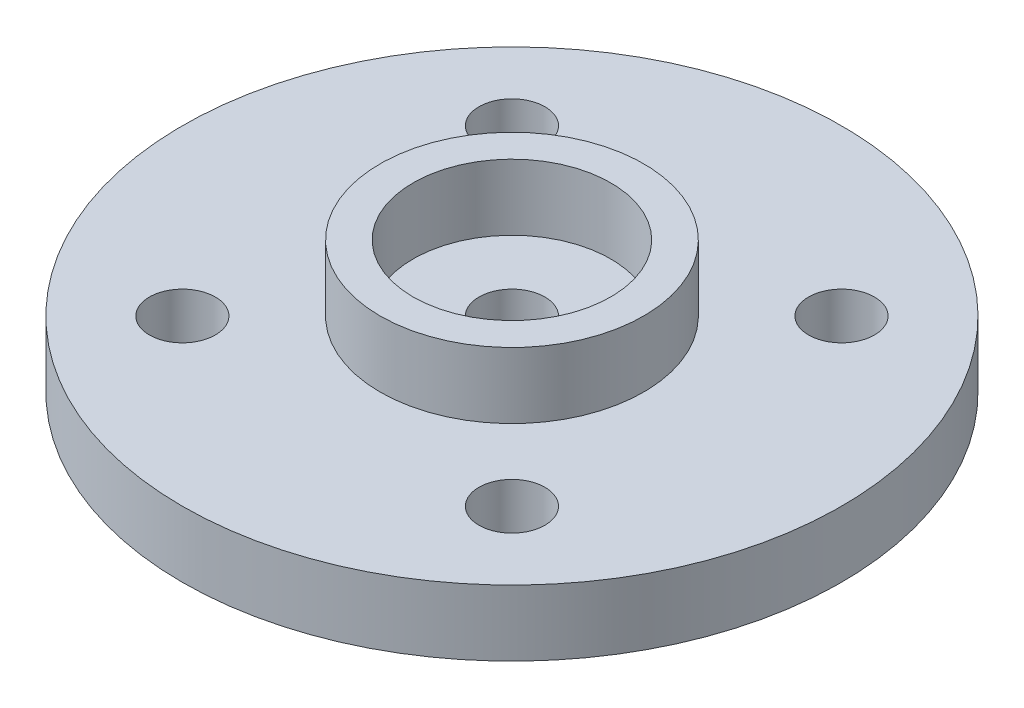
SolidWorks part; units mm, degrees
ref_plane "前视基准面" through (0, 0, 0) normal (0, 0, 1) x (1, 0, 0)
ref_plane "上视基准面" through (0, 0, 0) normal (0, 1, 0) x (1, 0, 0)
ref_plane "右视基准面" through (0, 0, 0) normal (1, 0, 0) x (0, 0, -1)
sketch "草图1" plane through (0, 0, 0) normal (0, 1, 0) x (1, 0, 0)
  line L1 (-5, 5) -> (5, 5) construction
  line L2 (-5, 5) -> (-5, -5) construction
  line L3 (-5, -5) -> (5, -5) construction
  line L4 (5, 5) -> (5, -5) construction
  line L5 (-5, 5) -> (5, -5) construction
  line L6 (-5, -5) -> (5, 5) construction
  circle A0 centre (0, 0) radius 1
  circle A1 centre (0, 0) radius 3.0838
  circle A2 centre (0, 0) radius 10
  circle A3 centre (-5, 5) radius 1
  circle A4 centre (5, 5) radius 1
  circle A5 centre (5, -5) radius 1
  circle A6 centre (-5, -5) radius 1
  point P19 (0, 0)
  dimension "D3" = 20
  dimension "D4" = 2
  dimension "D5" = 2
  dimension "D1" = 10
  dimension "D2" = 10
  dimension "D6" = 4
extrude "凸台-拉伸1" add sketch "草图1" along normal blind 2 contours A2 A6 A5 A4 A3 A1 | A1 A0
ref_plane "基准面1" through (0, 2, 0) normal (0, 1, 0) x (1, 0, 0)
sketch "草图2" plane through (0, 2, 0) normal (0, 1, 0) x (1, 0, 0)
  circle A0 centre (0, 0) radius 1
  circle A1 centre (0, 0) radius 3
  circle A2 centre (0, 0) radius 4
  dimension "D1" = 8
  dimension "D2" = 2
  dimension "D3" = 6
extrude "凸台-拉伸2" add sketch "草图2" along normal blind 2 contours A2 A1
